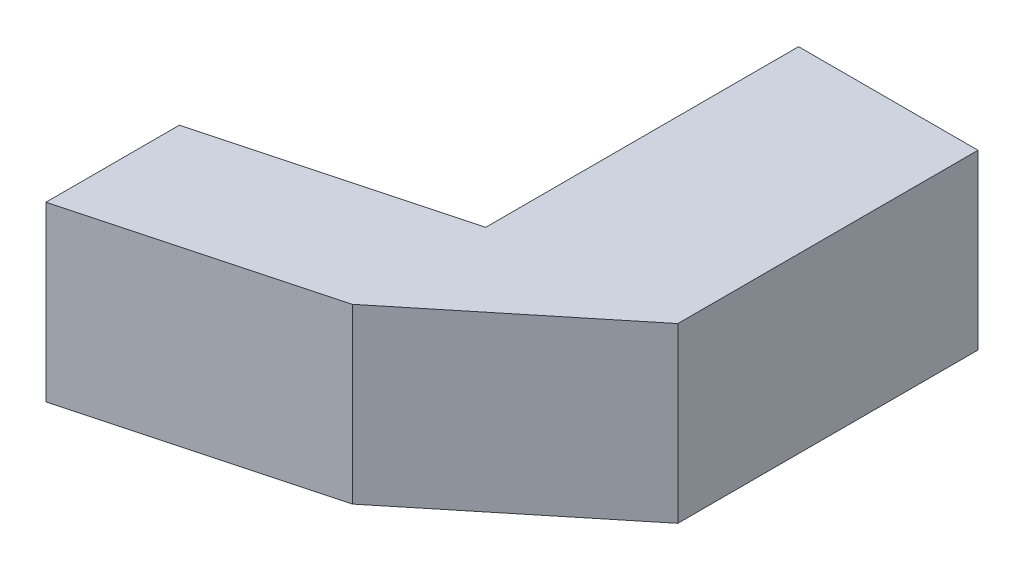
SolidWorks part; units mm, degrees
ref_plane "Front Plane" through (0, 0, 0) normal (0, 0, 1) x (1, 0, 0)
ref_plane "Top Plane" through (0, 0, 0) normal (0, 1, 0) x (1, 0, 0)
ref_plane "Right Plane" through (0, 0, 0) normal (1, 0, 0) x (0, 0, -1)
sketch "Sketch1" plane through (0, 0, 0) normal (0, 0, 1) x (1, 0, 0)
  line L0 (-5.3795, -5.1875) -> (-5.3795, 5.1875)
  line L1 (-3.3795, -3.1875) -> (3.3795, -3.1875)
  line L2 (-3.3795, -3.1875) -> (-3.3795, 3.1875)
  line L3 (-3.3795, 3.1875) -> (3.3795, 3.1875)
  line L4 (3.3795, -3.1875) -> (3.3795, 3.1875)
  line L5 (-3.3795, -3.1875) -> (3.3795, 3.1875) construction
  line L6 (-3.3795, 3.1875) -> (3.3795, -3.1875) construction
  line L7 (-5.3795, 5.1875) -> (5.3795, 5.1875)
  line L8 (5.3795, -5.1875) -> (5.3795, 5.1875)
  line L9 (-5.3795, -5.1875) -> (5.3795, -5.1875)
  point P0 (0, 0)
  dimension "D1" = 6.375
  dimension "D2" = 6.7589
  dimension "D3" = 2
extrude "Boss-Extrude1" add sketch "Sketch1" along normal blind 18 contours L0 L7 L8 L9 | L2 L1 L4 L3
sketch "Sketch2" plane through (0, -3.1875, 0) normal (0, 1, 0) x (1, 0, 0)
  line L0 (3.3795, -18) -> (-3.5502, -24.9296)
  line L3 (3.3795, -18) -> (-3.3795, -18)
  line L4 (-3.5502, -24.9296) -> (-3.3795, -18)
  dimension "D1" = 45
  dimension "D2" = 9.8
extrude "Boss-Extrude2" add sketch "Sketch2" against normal up to surface (2 mm away) up to face at (0, -5.1875, 9)
sketch "Sketch3" plane through (0, 0, 18) normal (0, 0, 1) x (1, 0, 0)
  line L1 (-3.3795, -3.1875) -> (3.3795, -3.1875)
  line L2 (-3.3795, -3.1875) -> (-3.3795, 3.1875)
  line L3 (-3.3795, 3.1875) -> (3.3795, 3.1875)
  line L4 (3.3795, -3.1875) -> (3.3795, 3.1875)
  line L5 (-3.3795, -3.1875) -> (3.3795, 3.1875) construction
  line L6 (-3.3795, 3.1875) -> (3.3795, -3.1875) construction
  line L7 (-5.3795, -5.1875) -> (5.3795, -5.1875)
  line L8 (-5.3795, -5.1875) -> (-5.3795, 5.1875)
  line L9 (-5.3795, 5.1875) -> (5.3795, 5.1875)
  line L10 (5.3795, -5.1875) -> (5.3795, 5.1875)
  line L11 (-5.3795, -5.1875) -> (5.3795, 5.1875) construction
  line L12 (-5.3795, 5.1875) -> (5.3795, -5.1875) construction
  point P0 (0, 0)
  point P7 (0, 0)
extrude "Boss-Extrude3" add sketch "Sketch3" along normal up to surface (8.7589 mm away) contours L8 L7 L10 L9 | L2 L1 L4 L3
sketch "Sketch7" plane through (0, -5.1875, 0) normal (0, -1, 0) x (-1, 0, 0)
  line L0 (5.3795, -26.7589) -> (19.8684, -30.6412)
  line L1 (19.8684, -30.6412) -> (19.8684, -22.6412)
  line L2 (19.8684, -22.6412) -> (5.3795, -18.7589)
  line L3 (5.3795, -26.7589) -> (5.3795, 0) construction
  line L9 (-3.3795, -18) -> (5.3795, -26.7589)
  line L10 (5.3795, -26.7589) -> (5.3795, 0)
  line L11 (5.3795, 0) -> (-5.3795, 0)
  line L12 (-5.3795, 0) -> (-5.3795, -18)
  line L13 (-5.3795, -18) -> (-3.3795, -18)
  line L15 (5.3795, -26.7589) -> (5.3795, -18.7589)
  dimension "D1" = 8
  dimension "D2" = 15
  dimension "D3" = 75
  dimension "D4" = 0
extrude "Boss-Extrude7" add sketch "Sketch7" against normal up to surface (10.375 mm away) up to face at (0.6759, 5.1875, 12.5518)
sketch "Sketch8" plane through (0, -5.1875, 0) normal (0, -1, 0) x (-1, 0, 0)
  line L0 (5.3795, -26.7589) -> (-5.3795, -18)
  line L1 (-5.3795, -18) -> (-3.3795, -18)
  line L2 (-3.3795, -18) -> (5.3795, -26.7589)
extrude "Boss-Extrude8" add sketch "Sketch8" against normal up to surface (10.375 mm away) up to face at (-5.2171, 5.1875, 16.85)
